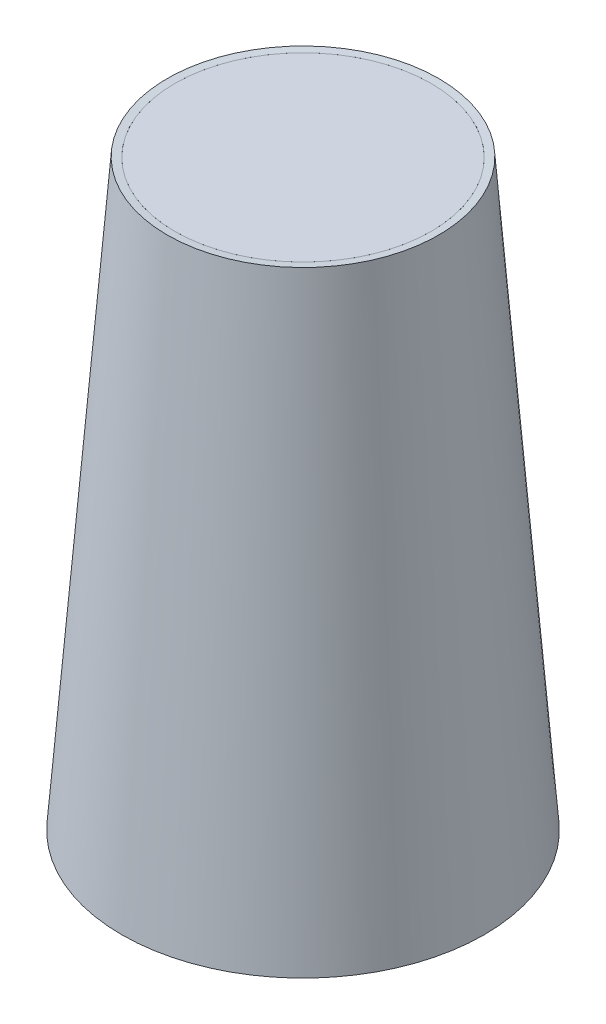
SolidWorks part; units mm, degrees
material "Par défaut"
ref_plane "Front Plane" through (0, 0, 0) normal (0, 0, 1) x (1, 0, 0)
ref_plane "Top Plane" through (0, 0, 0) normal (0, 1, 0) x (1, 0, 0)
ref_plane "Right Plane" through (0, 0, 0) normal (1, 0, 0) x (0, 0, -1)
ref_plane "Plan2" through (0, 0, 237.8791) normal (0, 0, 1) x (1, 0, 0)
sketch "Esquisse5" plane through (0, 0, 237.8791) normal (0, 0, 1) x (1, 0, 0)
  line L0 (-354.2793, 44.6121) -> (-379.7793, 44.6121)
  line L1 (-379.7793, 44.6121) -> (-379.7793, 43.1121)
  line L2 (-379.7793, 43.1121) -> (-354.2793, 43.1121)
  line L3 (-354.2793, 43.1121) -> (-354.2793, 44.6121)
  line L4 (-379.7793, 44.6121) -> (-379.7793, 43.1121) construction
revolve "Révolution2" add sketch "Esquisse5" angle 360 about L1
ref_plane "Plan3" through (0, 0, 237.8791) normal (0, 0, -1) x (-1, 0, 0)
sketch "Esquisse10" plane through (0, 0, 237.8791) normal (0, 0, -1) x (-1, 0, 0)
  line L0 (343.7075, -71.3169) -> (345.2029, -71.4338)
  line L1 (345.2029, -71.4338) -> (354.2748, 44.6121)
  line L2 (354.2748, 44.6121) -> (352.7793, 44.729)
  line L3 (352.7793, 44.729) -> (343.7075, -71.3169)
  line L4 (379.7793, -71.4338) -> (379.7793, 44.729) construction
revolve "Révolution3" add sketch "Esquisse10" angle 360 about L4
